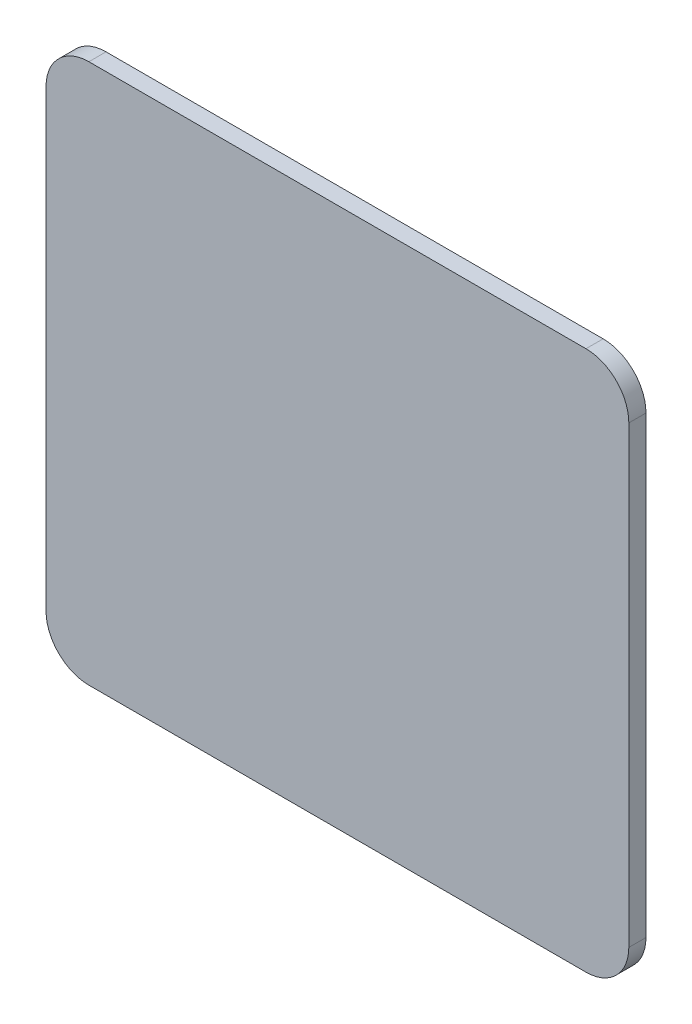
SolidWorks part; units mm, degrees
ref_plane "Front Plane" through (0, 0, 0) normal (0, 0, 1) x (1, 0, 0)
ref_plane "Top Plane" through (0, 0, 0) normal (0, 1, 0) x (1, 0, 0)
ref_plane "Right Plane" through (0, 0, 0) normal (1, 0, 0) x (0, 0, -1)
sketch "Sketch1" plane through (0, 0, 0) normal (0, 0, 1) x (1, 0, 0)
  line L0 (-9.7465, 16.9401) -> (19.2535, 16.9401)
  line L5 (21.7535, 14.4401) -> (21.7535, -12.0599)
  line L6 (-9.7465, -14.5599) -> (19.2535, -14.5599)
  line L7 (-12.2465, 14.4401) -> (-12.2465, -12.0599)
  arc A4 (19.2535, 16.9401) -> (21.7535, 14.4401) centre (19.2535, 14.4401) cw
  arc A5 (19.2535, -14.5599) -> (21.7535, -12.0599) centre (19.2535, -12.0599) ccw
  arc A6 (-12.2465, -12.0599) -> (-9.7465, -14.5599) centre (-9.7465, -12.0599) ccw
  arc A7 (-9.7465, 16.9401) -> (-12.2465, 14.4401) centre (-9.7465, 14.4401) ccw
extrude "Boss-Extrude1" add sketch "Sketch1" along normal blind 1
